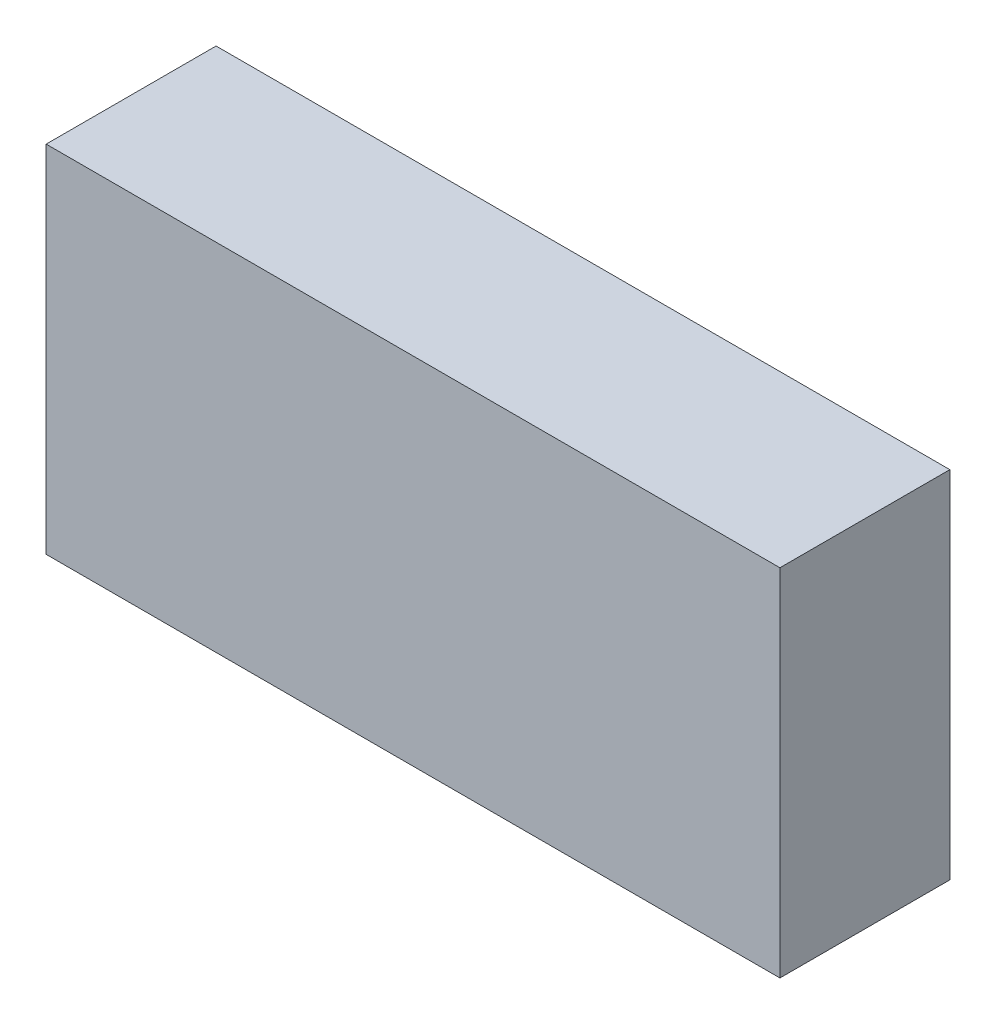
SolidWorks part; units mm, degrees
ref_plane "Front Plane" through (0, 0, 0) normal (0, 0, 1) x (1, 0, 0)
ref_plane "Top Plane" through (0, 0, 0) normal (0, 1, 0) x (1, 0, 0)
ref_plane "Right Plane" through (0, 0, 0) normal (1, 0, 0) x (0, 0, -1)
sketch "Sketch1" plane through (0, 0, 0) normal (0, 0, 1) x (1, 0, 0)
  line L1 (-47.5, 23) -> (47.5, 23)
  line L2 (-47.5, 23) -> (-47.5, -23)
  line L3 (-47.5, -23) -> (47.5, -23)
  line L4 (47.5, 23) -> (47.5, -23)
  line L5 (-47.5, 23) -> (47.5, -23) construction
  line L6 (-47.5, -23) -> (47.5, 23) construction
  point P0 (0, 0)
  dimension "D1" = 46
  dimension "D2" = 95
extrude "Boss-Extrude1" add sketch "Sketch1" along normal blind 22
